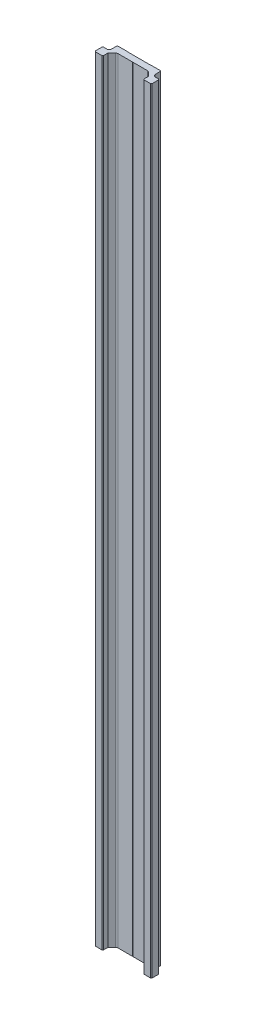
SolidWorks part; units mm, degrees
ref_plane "Front Plane" through (0, 0, 0) normal (0, 0, 1) x (1, 0, 0)
ref_plane "Top Plane" through (0, 0, 0) normal (0, 1, 0) x (1, 0, 0)
ref_plane "Right Plane" through (0, 0, 0) normal (1, 0, 0) x (0, 0, -1)
ref_plane "Plane1" through (0, 200, 0) normal (0, 1, 0) x (1, 0, 0)
sketch "Sketch1" plane through (0, 200, 0) normal (0, 1, 0) x (1, 0, 0)
  line L0 (0, -3.8557) -> (0.25, -4)
  line L1 (0.25, -4) -> (9.0787, -4)
  line L2 (10.1394, -4.4394) -> (12.5, -6.8)
  line L3 (12.5, -6.8) -> (12.5, -9.5)
  line L4 (12.5, -9.5) -> (13, -10)
  line L5 (13, -10) -> (17, -10)
  line L6 (17, -10) -> (17.5, -9.5)
  line L7 (17.5, -9.5) -> (17.5, -5.5)
  line L8 (17.5, -5.5) -> (17, -5)
  line L9 (17, -5) -> (14.3, -5)
  line L10 (14.3, -5) -> (14.0858, -4.7858)
  line L11 (13.5, -3.3716) -> (13.5, -0.3)
  line L12 (13.5, -0.3) -> (13.2, 0)
  line L13 (13.2, 0) -> (7.5, 0)
  line L14 (7.5, 0) -> (7.4, -0.1)
  line L15 (7.4, -0.1) -> (-7.4, -0.1)
  line L16 (-7.4, -0.1) -> (-7.5, 0)
  line L17 (-7.5, 0) -> (-13.2, 0)
  line L18 (-13.2, 0) -> (-13.5, -0.3)
  line L19 (-13.5, -0.3) -> (-13.5, -3.3716)
  line L20 (-14.0858, -4.7858) -> (-14.3, -5)
  line L21 (-14.3, -5) -> (-17, -5)
  line L22 (-17, -5) -> (-17.5, -5.5)
  line L23 (-17.5, -5.5) -> (-17.5, -9.5)
  line L24 (-17.5, -9.5) -> (-17, -10)
  line L25 (-17, -10) -> (-13, -10)
  line L26 (-13, -10) -> (-12.5, -9.5)
  line L27 (-12.5, -9.5) -> (-12.5, -6.8)
  line L28 (-12.5, -6.8) -> (-10.1394, -4.4394)
  line L29 (-9.0787, -4) -> (-0.25, -4)
  line L30 (-0.25, -4) -> (0, -3.8557)
  arc A0 (9.0787, -4) -> (10.1394, -4.4394) centre (9.0787, -5.5) cw
  arc A1 (14.0858, -4.7858) -> (13.5, -3.3716) centre (15.5, -3.3716) cw
  arc A2 (-13.5, -3.3716) -> (-14.0858, -4.7858) centre (-15.5, -3.3716) cw
  arc A3 (-10.1394, -4.4394) -> (-9.0787, -4) centre (-9.0787, -5.5) cw
extrude "Boss-Extrude1" add sketch "Sketch1" against normal blind 478
ref_plane "Plane2" through (0, 210, 0) normal (0, 1, 0) x (1, 0, 0)
